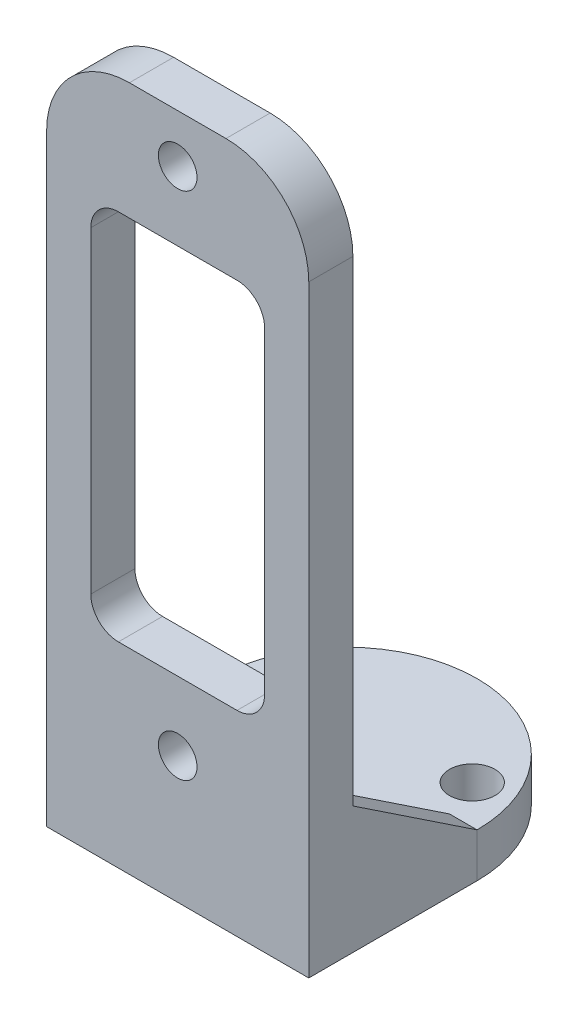
SolidWorks part; units mm, degrees
ref_plane "Front Plane" through (0, 0, 0) normal (0, 0, 1) x (1, 0, 0)
ref_plane "Top Plane" through (0, 0, 0) normal (0, 1, 0) x (1, 0, 0)
ref_plane "Right Plane" through (0, 0, 0) normal (1, 0, 0) x (0, 0, -1)
sketch "Sketch1" plane through (0, 0, 0) normal (0, 0, 1) x (1, 0, 0)
  line L0 (9.5, 0) -> (9.5, 6) construction
  line L1 (0, 0) -> (19, 0)
  line L2 (0, 0) -> (0, 40.5)
  line L3 (6, 46.5) -> (13, 46.5)
  line L4 (19, 0) -> (19, 40.5)
  circle A0 centre (9.5, 6) radius 1.4
  circle A1 centre (9.5, 43) radius 1.4
  arc A2 (13, 46.5) -> (19, 40.5) centre (13, 40.5) cw
  arc A3 (0, 40.5) -> (6, 46.5) centre (6, 40.5) cw
  dimension "D3" = 2.8
  dimension "D7" = 6
  dimension "D1" = 19
  dimension "D2" = 46.5
  dimension "D4" = 6
  dimension "D6" = 37
  dimension "D5" = 2
extrude "Boss-Extrude1" add sketch "Sketch1" along normal blind 3.2
sketch "Sketch2" plane through (0, 0, 0) normal (0, 1, 0) x (1, 0, 0)
  line L0 (0, 9) -> (0, -3.2)
  line L1 (0, -3.2) -> (19, -3.2)
  line L3 (19, -3.2) -> (19, 9)
  line L4 (13, 0) -> (6, 0) construction
  arc A1 (19, 9) -> (0, 9) centre (9.5, 9) ccw
  dimension "D2" = 9
extrude "Boss-Extrude3" add sketch "Sketch2" against normal blind 3.2
sketch "Sketch3" plane through (0, 0, 0) normal (1, 0, 0) x (0, 0, -1)
  line L0 (0, 0) -> (9, 0)
  line L2 (9, 0) -> (0, 6)
  line L4 (0, 6) -> (0, 0)
  dimension "D1" = 6
extrude "Boss-Extrude4" add sketch "Sketch3" along normal blind 2
pattern_linear "LPattern1" count 2 spacing 17 along (1, 0, 0) of "Boss-Extrude4"
sketch "Sketch4" plane through (0, 0, 0) normal (0, 0, 1) x (1, 0, 0)
  line L0 (0, 40.5) -> (0, -3.2) construction
  line L1 (5.2, 38) -> (13.8, 38)
  line L2 (3.2, 36) -> (3.2, 13)
  line L3 (5.2, 11) -> (13.8, 11)
  line L4 (15.8, 36) -> (15.8, 13)
  line L5 (19, -3.2) -> (19, 40.5) construction
  circle A0 centre (9.5, 6) radius 1.4 construction
  circle A1 centre (9.5, 43) radius 1.4 construction
  arc A2 (3.2, 13) -> (5.2, 11) centre (5.2, 13) ccw
  arc A3 (13.8, 11) -> (15.8, 13) centre (13.8, 13) ccw
  arc A4 (13.8, 38) -> (15.8, 36) centre (13.8, 36) cw
  arc A5 (5.2, 38) -> (3.2, 36) centre (5.2, 36) ccw
  dimension "D3" = 5
  dimension "D5" = 2
  dimension "D1" = 3.2
  dimension "D2" = 3.2
  dimension "D4" = 5
extrude "Cut-Extrude1" cut sketch "Sketch4" along normal through all
sketch "Sketch8" plane through (0, 0, 0) normal (0, 1, 0) x (1, 0, 0)
  line L0 (0, 9) -> (0, -3.2) construction
  line L1 (0, -3.2) -> (19, -3.2) construction
  line L2 (9.5, -3.2) -> (9.5, 18.5) construction
  line L3 (13, -3.2) -> (6, -3.2) construction
  circle A0 centre (3.15, 11.8) radius 1.65
  circle A1 centre (14.1485, 5.45) radius 1.65
  circle A2 centre (4.8515, 5.45) radius 1.65
  arc A3 (19, 9) -> (0, 9) centre (9.5, 9) ccw construction
  circle A4 centre (15.85, 11.8) radius 1.65
  dimension "D1" = 3.3
  dimension "D4" = 3.3
  dimension "D6" = 8.65
  dimension "D7" = 3.3
  dimension "D8" = 8.65
  dimension "D9" = 10.9985
  dimension "D2" = 3.15
  dimension "D3" = 15
  dimension "D5" = 10.9985
extrude "Cut-Extrude4" cut sketch "Sketch8" against normal through all both and the other way through all
